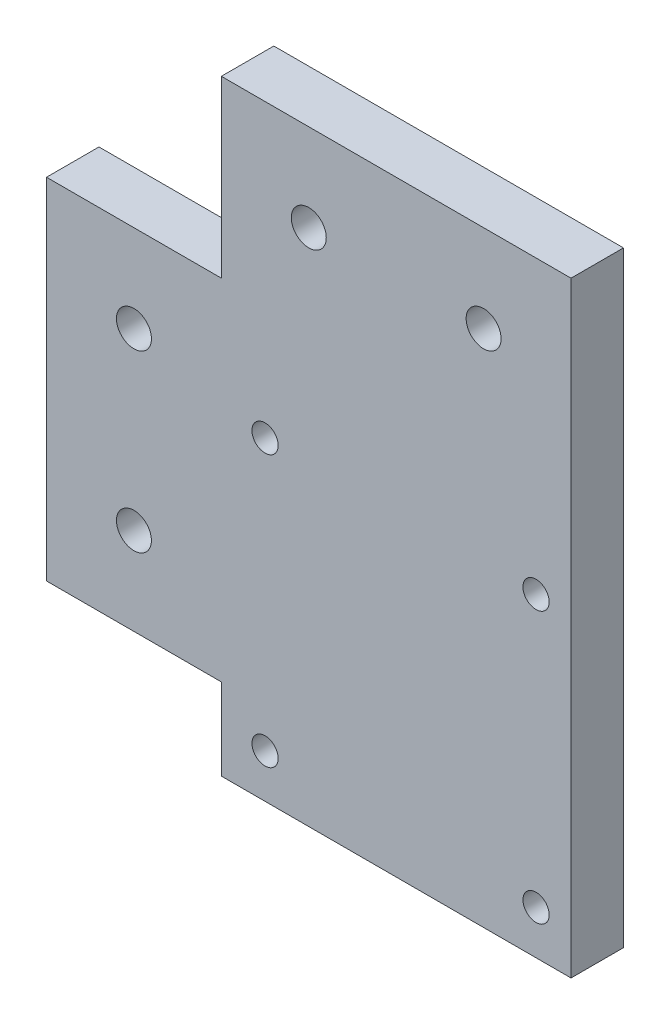
SolidWorks part; units mm, degrees
ref_plane "Front Plane" through (0, 0, 0) normal (0, 0, 1) x (1, 0, 0)
ref_plane "Top Plane" through (0, 0, 0) normal (0, 1, 0) x (1, 0, 0)
ref_plane "Right Plane" through (0, 0, 0) normal (1, 0, 0) x (0, 0, -1)
sketch "Sketch1" plane through (0, 0, 0) normal (0, 0, 1) x (1, 0, 0)
  line L0 (20, -60) -> (60, -20) construction
  line L1 (20, 0) -> (60, 0)
  line L2 (0, -20) -> (0, -60)
  line L3 (0, -60) -> (20, -60)
  line L4 (60, 0) -> (60, -20)
  line L5 (10, -60) -> (10, -50) construction
  line L6 (10, -50) -> (10, -30) construction
  line L7 (10, -30) -> (10, -10) construction
  line L8 (10, -10) -> (30, -10) construction
  line L9 (30, -10) -> (50, -10) construction
  line L10 (50, -10) -> (60, -10) construction
  line L11 (60, -20) -> (60, -69.3319)
  line L15 (0, -60) -> (0, -20) construction
  line L16 (20, -69.3319) -> (60, -69.3319)
  line L17 (20, -69.3319) -> (20, -60)
  line L21 (0, -20) -> (20, -20)
  line L22 (20, 0) -> (20, -20)
  line L23 (20, 0) -> (0, 0) construction
  line L24 (0, -20) -> (0, 0) construction
  circle A0 centre (50, -10) radius 2
  circle A1 centre (30, -10) radius 2
  circle A2 centre (10, -50) radius 2
  circle A3 centre (10, -30) radius 2
  circle A4 centre (25, -64.3319) radius 1.5
  circle A5 centre (24.9973, -33.3319) radius 1.5
  circle A6 centre (56, -64.3319) radius 1.5
  circle A7 centre (55.9973, -33.3319) radius 1.5
  dimension "D3" = 4
  dimension "D10" = 4.0027
  dimension "D12" = 3
  dimension "D14" = 5
  dimension "D16" = 5
  dimension "D17" = 31
  dimension "D18" = 20
  dimension "D19" = 31
  dimension "D20" = 31
  dimension "D1" = 60
  dimension "D2" = 20
  dimension "D4" = 10
  dimension "D5" = 30
  dimension "D6" = 30
  dimension "D7" = 10
  dimension "D8" = 60
  dimension "D9" = 20
  dimension "D11" = 69.3319
  dimension "D13" = 5
  dimension "D15" = 31
extrude "Boss-Extrude1" add sketch "Sketch1" along normal blind 6
